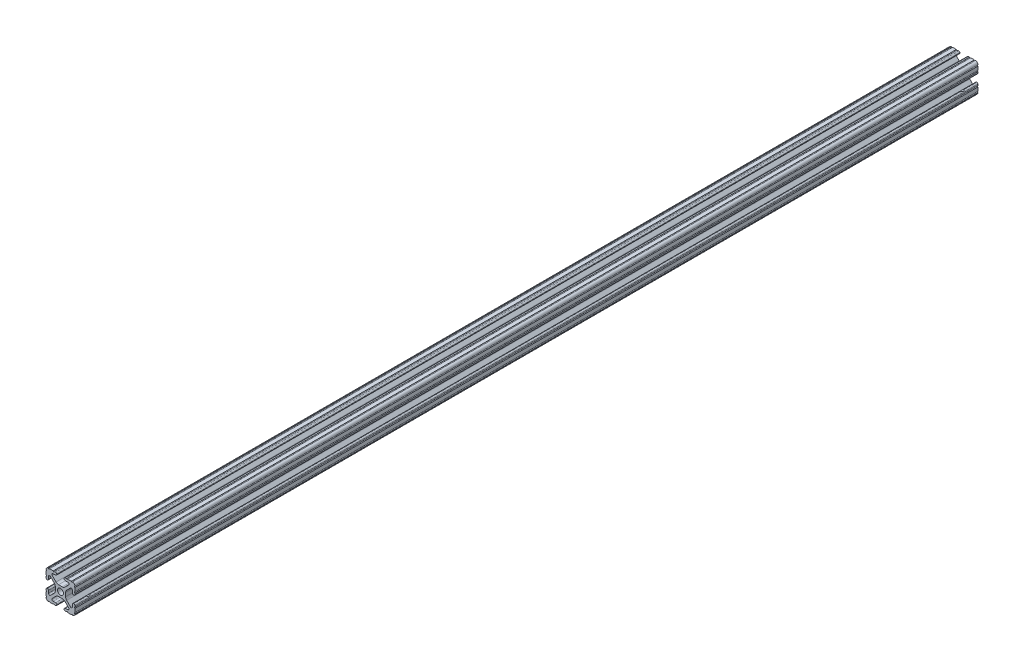
SolidWorks part; units mm, degrees
ref_plane "Front Plane" through (0, 0, 0) normal (0, 0, 1) x (1, 0, 0)
ref_plane "Top Plane" through (0, 0, 0) normal (0, 1, 0) x (1, 0, 0)
ref_plane "Right Plane" through (0, 0, 0) normal (1, 0, 0) x (0, 0, -1)
sketch "Sketch1" plane through (0, 0, 0) normal (0, 0, 1) x (1, 0, 0)
  line L88 (-7.1797, -8.6452) -> (-3.9523, -5.4237)
  line L89 (-1.7093, -4.4958) -> (1.7093, -4.4958)
  line L90 (3.9523, -5.4237) -> (7.1797, -8.6452)
  line L91 (6.4164, -10.4902) -> (4.2875, -10.4902)
  line L92 (3.2385, -11.5392) -> (3.2385, -11.651)
  line L93 (4.2875, -12.7) -> (5.3171, -12.7)
  line L94 (6.3331, -12.7) -> (9.5504, -12.7)
  line L95 (12.7, -9.5504) -> (12.7, -6.3331)
  line L96 (12.7, -5.3171) -> (12.7, -4.2875)
  line L97 (11.651, -3.2385) -> (11.5392, -3.2385)
  line L98 (10.4902, -4.2875) -> (10.4902, -6.4021)
  line L99 (8.7371, -7.1294) -> (5.441, -3.8408)
  line L100 (4.5085, -1.5932) -> (4.5085, 1.5932)
  line L101 (5.441, 3.8408) -> (8.7371, 7.1294)
  line L102 (10.4902, 6.4021) -> (10.4902, 4.2875)
  line L103 (11.5392, 3.2385) -> (11.651, 3.2385)
  line L104 (12.7, 4.2875) -> (12.7, 5.3171)
  line L105 (12.7, 6.3331) -> (12.7, 9.5504)
  line L106 (9.5504, 12.7) -> (6.3331, 12.7)
  line L107 (5.3171, 12.7) -> (4.2875, 12.7)
  line L108 (3.2385, 11.651) -> (3.2385, 11.5392)
  line L109 (4.2875, 10.4902) -> (6.4768, 10.4902)
  line L110 (7.207, 8.7244) -> (3.8983, 5.4232)
  line L111 (1.6558, 4.4958) -> (-1.6558, 4.4958)
  line L112 (-3.8983, 5.4232) -> (-7.207, 8.7244)
  line L113 (-6.4768, 10.4902) -> (-4.2875, 10.4902)
  line L114 (-3.2385, 11.5392) -> (-3.2385, 11.651)
  line L115 (-4.2875, 12.7) -> (-5.3171, 12.7)
  line L116 (-6.3331, 12.7) -> (-9.5504, 12.7)
  line L117 (-12.7, 9.5504) -> (-12.7, 6.3331)
  line L118 (-12.7, 5.3171) -> (-12.7, 4.2875)
  line L119 (-11.651, 3.2385) -> (-11.5392, 3.2385)
  line L120 (-10.4902, 4.2875) -> (-10.4902, 6.4021)
  line L121 (-8.7371, 7.1294) -> (-5.441, 3.8408)
  line L122 (-4.5085, 1.5932) -> (-4.5085, -1.5932)
  line L123 (-5.441, -3.8408) -> (-8.7371, -7.1294)
  line L124 (-10.4902, -6.4021) -> (-10.4902, -4.2875)
  line L125 (-11.5392, -3.2385) -> (-11.651, -3.2385)
  line L126 (-12.7, -4.2875) -> (-12.7, -5.3171)
  line L127 (-12.7, -6.3331) -> (-12.7, -9.5504)
  line L128 (-9.5504, -12.7) -> (-6.3331, -12.7)
  line L129 (-5.3171, -12.7) -> (-4.2875, -12.7)
  line L130 (-3.2385, -11.651) -> (-3.2385, -11.5392)
  line L131 (-4.2875, -10.4902) -> (-6.4164, -10.4902)
  circle A1 centre (0, 0) radius 2.6035
  arc A104 (-7.1797, -8.6452) -> (-6.4164, -10.4902) centre (-6.4164, -9.4098) ccw
  arc A105 (-1.7093, -4.4958) -> (-3.9523, -5.4237) centre (-1.7093, -7.6708) ccw
  arc A106 (3.9523, -5.4237) -> (1.7093, -4.4958) centre (1.7093, -7.6708) ccw
  arc A107 (6.4164, -10.4902) -> (7.1797, -8.6452) centre (6.4164, -9.4098) ccw
  arc A108 (4.2875, -10.4902) -> (3.2385, -11.5392) centre (4.2875, -11.5392) ccw
  arc A109 (3.2385, -11.651) -> (4.2875, -12.7) centre (4.2875, -11.651) ccw
  arc A110 (6.3331, -12.7) -> (5.3171, -12.7) centre (5.8251, -12.7) ccw
  arc A111 (10.5664, -12.6998) -> (9.5504, -12.7) centre (10.0584, -12.7) ccw
  arc A112 (10.5664, -12.6998) -> (12.6998, -10.5664) centre (10.5918, -10.5918) ccw
  arc A113 (12.7, -9.5504) -> (12.6998, -10.5664) centre (12.7, -10.0584) ccw
  arc A114 (12.7, -5.3171) -> (12.7, -6.3331) centre (12.7, -5.8251) ccw
  arc A115 (12.7, -4.2875) -> (11.651, -3.2385) centre (11.651, -4.2875) ccw
  arc A116 (11.5392, -3.2385) -> (10.4902, -4.2875) centre (11.5392, -4.2875) ccw
  arc A117 (8.7371, -7.1294) -> (10.4902, -6.4021) centre (9.4628, -6.4021) ccw
  arc A118 (4.5085, -1.5932) -> (5.441, -3.8408) centre (7.6835, -1.5932) ccw
  arc A119 (5.441, 3.8408) -> (4.5085, 1.5932) centre (7.6835, 1.5932) ccw
  arc A120 (10.4902, 6.4021) -> (8.7371, 7.1294) centre (9.4628, 6.4021) ccw
  arc A121 (10.4902, 4.2875) -> (11.5392, 3.2385) centre (11.5392, 4.2875) ccw
  arc A122 (11.651, 3.2385) -> (12.7, 4.2875) centre (11.651, 4.2875) ccw
  arc A123 (12.7, 6.3331) -> (12.7, 5.3171) centre (12.7, 5.8251) ccw
  arc A124 (12.6998, 10.5664) -> (12.7, 9.5504) centre (12.7, 10.0584) ccw
  arc A125 (12.6998, 10.5664) -> (10.5664, 12.6998) centre (10.5918, 10.5918) ccw
  arc A126 (9.5504, 12.7) -> (10.5664, 12.6998) centre (10.0584, 12.7) ccw
  arc A127 (5.3171, 12.7) -> (6.3331, 12.7) centre (5.8251, 12.7) ccw
  arc A128 (4.2875, 12.7) -> (3.2385, 11.651) centre (4.2875, 11.651) ccw
  arc A129 (3.2385, 11.5392) -> (4.2875, 10.4902) centre (4.2875, 11.5392) ccw
  arc A130 (7.207, 8.7244) -> (6.4768, 10.4902) centre (6.4768, 9.4563) ccw
  arc A131 (1.6558, 4.4958) -> (3.8983, 5.4232) centre (1.6558, 7.6708) ccw
  arc A132 (-3.8983, 5.4232) -> (-1.6558, 4.4958) centre (-1.6558, 7.6708) ccw
  arc A133 (-6.4768, 10.4902) -> (-7.207, 8.7244) centre (-6.4768, 9.4563) ccw
  arc A134 (-4.2875, 10.4902) -> (-3.2385, 11.5392) centre (-4.2875, 11.5392) ccw
  arc A135 (-3.2385, 11.651) -> (-4.2875, 12.7) centre (-4.2875, 11.651) ccw
  arc A136 (-6.3331, 12.7) -> (-5.3171, 12.7) centre (-5.8251, 12.7) ccw
  arc A137 (-10.5664, 12.6998) -> (-9.5504, 12.7) centre (-10.0584, 12.7) ccw
  arc A138 (-10.5664, 12.6998) -> (-12.6998, 10.5664) centre (-10.5918, 10.5918) ccw
  arc A139 (-12.7, 9.5504) -> (-12.6998, 10.5664) centre (-12.7, 10.0584) ccw
  arc A140 (-12.7, 5.3171) -> (-12.7, 6.3331) centre (-12.7, 5.8251) ccw
  arc A141 (-12.7, 4.2875) -> (-11.651, 3.2385) centre (-11.651, 4.2875) ccw
  arc A142 (-11.5392, 3.2385) -> (-10.4902, 4.2875) centre (-11.5392, 4.2875) ccw
  arc A143 (-8.7371, 7.1294) -> (-10.4902, 6.4021) centre (-9.4628, 6.4021) ccw
  arc A144 (-4.5085, 1.5932) -> (-5.441, 3.8408) centre (-7.6835, 1.5932) ccw
  arc A145 (-5.441, -3.8408) -> (-4.5085, -1.5932) centre (-7.6835, -1.5932) ccw
  arc A146 (-10.4902, -6.4021) -> (-8.7371, -7.1294) centre (-9.4628, -6.4021) ccw
  arc A147 (-10.4902, -4.2875) -> (-11.5392, -3.2385) centre (-11.5392, -4.2875) ccw
  arc A148 (-11.651, -3.2385) -> (-12.7, -4.2875) centre (-11.651, -4.2875) ccw
  arc A149 (-12.7, -6.3331) -> (-12.7, -5.3171) centre (-12.7, -5.8251) ccw
  arc A150 (-12.6998, -10.5664) -> (-12.7, -9.5504) centre (-12.7, -10.0584) ccw
  arc A151 (-12.6998, -10.5664) -> (-10.5664, -12.6998) centre (-10.5918, -10.5918) ccw
  arc A152 (-9.5504, -12.7) -> (-10.5664, -12.6998) centre (-10.0584, -12.7) ccw
  arc A153 (-5.3171, -12.7) -> (-6.3331, -12.7) centre (-5.8251, -12.7) ccw
  arc A154 (-4.2875, -12.7) -> (-3.2385, -11.651) centre (-4.2875, -11.651) ccw
  arc A155 (-3.2385, -11.5392) -> (-4.2875, -10.4902) centre (-4.2875, -11.5392) ccw
extrude "Boss-Extrude1" add sketch "Sketch1" along normal mid plane 793.47
sketch "Sketch2" plane through (4.5085, 0, 0) normal (1, 0, 0) x (0, 0, -1)
  line L0 (-396.735, -1.5932) -> (-396.735, 1.5932) construction
  line L1 (0, -1.5932) -> (0, 73.5485) construction
  line L2 (-396.735, -1.5932) -> (396.735, -1.5932) construction
  circle A0 centre (-384.035, 0) radius 3.5
  circle A1 centre (384.035, 0) radius 3.5
  dimension "D1" = 12.7
  dimension "D2" = 7
extrude "Cut-Extrude1" cut sketch "Sketch2" against normal through all both and the other way through all
